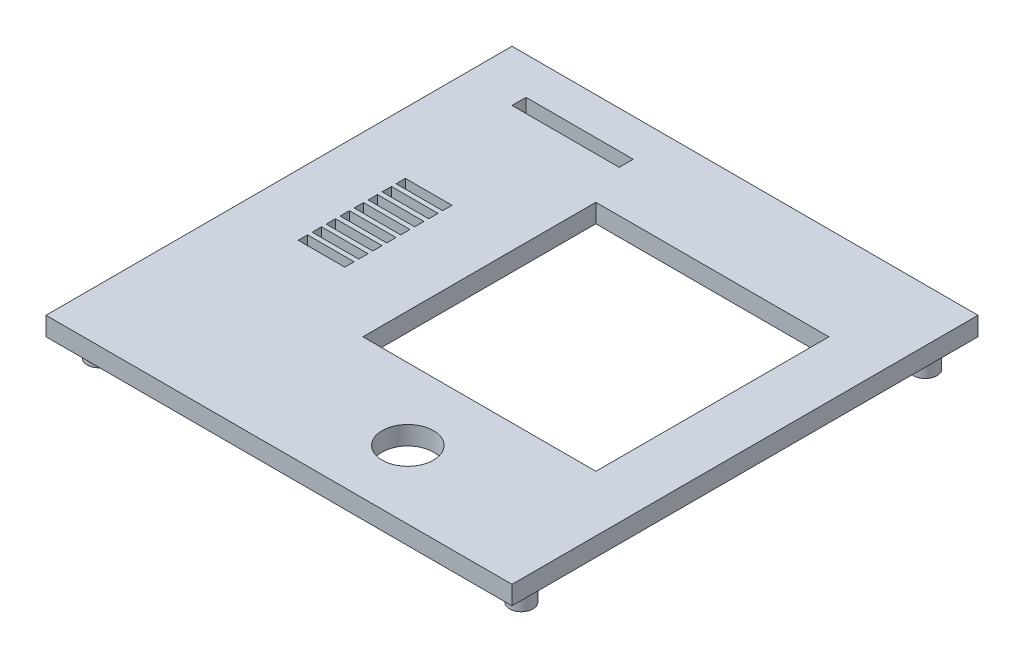
SolidWorks part; units mm, degrees
ref_plane "Front Plane" through (0, 0, 0) normal (0, 0, 1) x (1, 0, 0)
ref_plane "Top Plane" through (0, 0, 0) normal (0, 1, 0) x (1, 0, 0)
ref_plane "Right Plane" through (0, 0, 0) normal (1, 0, 0) x (0, 0, -1)
sketch "Sketch2" plane through (0, 0, 0) normal (0, 1, 0) x (1, 0, 0)
  line L1 (-50, 50) -> (50, 50)
  line L2 (-50, 50) -> (-50, -50)
  line L3 (-50, -50) -> (50, -50)
  line L4 (50, 50) -> (50, -50)
  line L5 (-50, 50) -> (50, -50) construction
  line L6 (-50, -50) -> (50, 50) construction
  point P0 (0, 0)
  dimension "D1" = 100
  dimension "D2" = 100
extrude "Boss-Extrude1" add sketch "Sketch2" along normal blind 4
sketch "Sketch3" plane through (0, 4, 0) normal (0, 1, 0) x (1, 0, 0)
  line L0 (50, -50) -> (50, 50) construction
  line L1 (50, 50) -> (-50, 50) construction
  line L3 (38, 30) -> (-12, 30)
  line L4 (38, 30) -> (38, -20)
  line L5 (38, -20) -> (-12, -20)
  line L6 (-12, 30) -> (-12, -20)
  point P0 (38, 30)
  dimension "D1" = 12
  dimension "D2" = 20
  dimension "D3" = 50
  dimension "D4" = 50
extrude "Cut-Extrude1" cut sketch "Sketch3" against normal blind 4
sketch "Sketch4" plane through (0, 4, 0) normal (0, 1, 0) x (1, 0, 0)
  line L0 (-50, 50) -> (-50, -50) construction
  line L1 (50, 50) -> (-50, 50) construction
  line L3 (-39, 42) -> (-16, 42)
  line L4 (-39, 42) -> (-39, 39)
  line L5 (-39, 39) -> (-16, 39)
  line L6 (-16, 42) -> (-16, 39)
  point P0 (-39, 42)
  dimension "D1" = 11
  dimension "D2" = 8
  dimension "D3" = 23
  dimension "D4" = 3
extrude "Cut-Extrude2" cut sketch "Sketch4" against normal blind 4
sketch "Sketch5" plane through (0, 4, 0) normal (0, 1, 0) x (1, 0, 0)
  line L0 (-39, 39) -> (-16, 39) construction
  line L1 (-36.8798, 14) -> (-26.8798, 14)
  line L2 (-36.8798, 14) -> (-36.8798, 12)
  line L3 (-36.8798, 12) -> (-26.8798, 12)
  line L4 (-26.8798, 14) -> (-26.8798, 12)
  dimension "D1" = 10
  dimension "D2" = 2
  dimension "D3" = 25
extrude "Cut-Extrude3" cut sketch "Sketch5" against normal blind 4
pattern_linear "LPattern1" count 8 spacing 3 along (0, 0, 1) of "Cut-Extrude3"
sketch "Sketch6" plane through (0, 4, 0) normal (0, 1, 0) x (1, 0, 0)
  line L0 (-50, 50) -> (-50, -50) construction
  circle A0 centre (13, -35.3616) radius 5.5
  dimension "D1" = 63
extrude "Cut-Extrude4" cut sketch "Sketch6" against normal blind 4 contours A0
sketch "Sketch8" plane through (0, 0, 0) normal (0, -1, 0) x (-1, 0, 0)
  line L0 (50, 50) -> (50, -50) construction
  line L1 (50, -50) -> (-50, -50) construction
  line L2 (-50, -50) -> (-50, 50) construction
  line L3 (-50, -50) -> (-50, 50) construction
  line L4 (-50, 50) -> (50, 50) construction
  line L6 (50, 50) -> (50, -50) construction
  circle A0 centre (45.34, 43.34) radius 2.5
  circle A1 centre (-45.34, 43.34) radius 2.5
  circle A2 centre (-45.34, -43.34) radius 2.5
  circle A3 centre (45.339, -43.339) radius 2.5
  point P0 (45.339, -43.339)
  point P1 (-45.34, -43.34)
  point P2 (-45.34, 43.34)
  point P3 (45.34, 43.34)
  dimension "D1" = 4.661
  dimension "D2" = 6.66
  dimension "D3" = 4.66
  dimension "D4" = 6.661
  dimension "D5" = 4.66
  dimension "D6" = 6.66
  dimension "D7" = 6.66
  dimension "D8" = 4.66
extrude "Boss-Extrude3" add sketch "Sketch8" along normal blind 5
sketch "Sketch10" plane through (0, 0, 0) normal (0, -1, 0) x (1, 0, 0)
  circle A0 centre (-45.34, -43.34) radius 1.5
  circle A1 centre (45.3188, -43.34) radius 1.5
extrude "Cut-Extrude5" cut sketch "Sketch10" against normal blind 3
sketch "Sketch11" plane through (0, 0, 0) normal (0, -1, 0) x (1, 0, 0)
  circle A0 centre (45.34, 43.34) radius 1.5
extrude "Cut-Extrude7" cut sketch "Sketch11" along normal blind 7
sketch "Sketch12" plane through (0, -5, 0) normal (0, -1, 0) x (1, 0, 0)
  circle A0 centre (45.34, -43.34) radius 1.5
extrude "Cut-Extrude8" cut sketch "Sketch12" against normal blind 4
sketch "Sketch13" plane through (0, -5, 0) normal (0, -1, 0) x (1, 0, 0)
  circle A0 centre (-45.34, -43.34) radius 1.5
extrude "Cut-Extrude9" cut sketch "Sketch13" against normal blind 4
sketch "Sketch14" plane through (0, -5, 0) normal (0, -1, 0) x (1, 0, 0)
  circle A0 centre (-45.339, 43.339) radius 1.5
extrude "Cut-Extrude10" cut sketch "Sketch14" against normal blind 4
